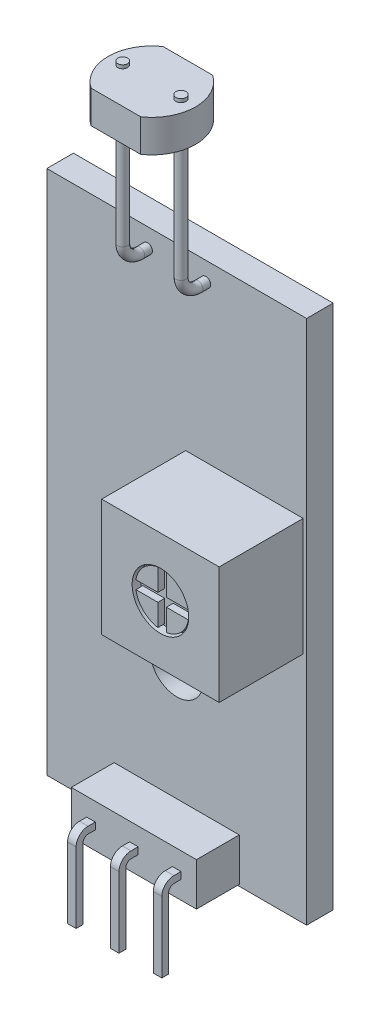
SolidWorks part; units mm, degrees
ref_plane "Plano frontal" through (0, 0, 0) normal (0, 0, 1) x (1, 0, 0)
ref_plane "Plano superior" through (0, 0, 0) normal (0, 1, 0) x (1, 0, 0)
ref_plane "Plano direito" through (0, 0, 0) normal (1, 0, 0) x (0, 0, -1)
sketch "Esboço1" plane through (0, 0, 0) normal (0, 0, 1) x (1, 0, 0)
  line L0 (0, -15.325) -> (0, -4.475) construction
  line L1 (7.575, 15.325) -> (-7.575, 15.325)
  line L2 (7.575, 15.325) -> (7.575, -15.325)
  line L3 (7.575, -15.325) -> (-7.575, -15.325)
  line L4 (-7.575, 15.325) -> (-7.575, -15.325)
  line L5 (7.575, 15.325) -> (-7.575, -15.325) construction
  line L6 (7.575, -15.325) -> (-7.575, 15.325) construction
  circle A0 centre (0, -6.025) radius 1.55
  point P0 (0, 0)
  dimension "D4" = 3.1
  dimension "D1" = 15.15
  dimension "D2" = 30.65
  dimension "D3" = 10.85
extrude "Ressalto-extrusão1" add sketch "Esboço1" along normal blind 1.55
sketch "Esboço2" plane through (0, 0, 0) normal (0, 0, 1) x (1, 0, 0)
  line L0 (7.575, -15.325) -> (7.575, 15.325) construction
  line L1 (7.375, 5.125) -> (0.525, 5.125)
  line L2 (7.375, 5.125) -> (7.375, -1.725)
  line L3 (7.375, -1.725) -> (0.525, -1.725)
  line L4 (0.525, 5.125) -> (0.525, -1.725)
  line L5 (-7.575, -15.325) -> (7.575, -15.325) construction
  dimension "D1" = 6.85
  dimension "D2" = 6.85
  dimension "D3" = 0.2
  dimension "D4" = 20.45
extrude "Ressalto-extrusão2" add sketch "Esboço2" along normal blind 6.45
sketch "Esboço3" plane through (0, 0, 6.45) normal (0, 0, 1) x (1, 0, 0)
  line L0 (0.525, -1.725) -> (7.375, 5.125) construction
  line L6 (3.7, 1.95) -> (2.4203, 1.95)
  line L7 (5.4797, 1.45) -> (4.2, 1.45)
  line L13 (5.4797, 1.95) -> (4.2, 1.95)
  line L15 (3.7, 1.45) -> (3.7, 0.1703)
  line L16 (4.2, 1.45) -> (4.2, 0.1703)
  line L19 (3.7, 3.2297) -> (3.7, 1.95)
  line L21 (4.2, 3.2297) -> (4.2, 1.95)
  line L22 (3.7, 1.45) -> (2.4203, 1.45)
  circle A0 centre (3.95, 1.7) radius 1.65
  arc A5 (5.4797, 1.95) -> (4.2, 3.2297) centre (3.95, 1.7) ccw
  circle A6 centre (3.95, 1.7) radius 1.55 construction
  arc A7 (2.4203, 1.45) -> (3.7, 0.1703) centre (3.95, 1.7) ccw
  arc A8 (4.2, 0.1703) -> (5.4797, 1.45) centre (3.95, 1.7) ccw
  arc A9 (3.7, 3.2297) -> (2.4203, 1.95) centre (3.95, 1.7) ccw
  point P7 (3.95, 1.7)
  dimension "D1" = 3.3
  dimension "D2" = 0.1
extrude "Corte-extrusão1" cut sketch "Esboço3" against normal blind 0.5
sketch "Esboço4" plane through (0, 0, 0) normal (0, 0, 1) x (1, 0, 0)
  line L2 (-3.65, -15.225) -> (-3.65, -12.725)
  line L3 (-3.65, -12.725) -> (3.65, -12.725)
  line L4 (3.65, -15.225) -> (3.65, -12.725)
  line L5 (0, -15.225) -> (0, -14.5169) construction
  line L6 (0, -15.225) -> (0, -11.5262) construction
  line L7 (-3.65, -15.225) -> (3.65, -15.225)
  line L8 (-7.575, -15.325) -> (7.575, -15.325) construction
  dimension "D1" = 7.3
  dimension "D2" = 0.1
  dimension "D3" = 2.5
extrude "Ressalto-extrusão3" add sketch "Esboço4" along normal blind 4.05
ref_plane "Plano1" through (0, 16.325, 0) normal (0, 1, 0) x (1, 0, 0)
sketch "Esboço9" plane through (0, 0, 6.45) normal (0, 0, 1) x (1, 0, 0)
  circle A1 centre (3.95, 1.7) radius 1.55
sketch "Esboço11" plane through (-3.65, 0, 0) normal (-1, 0, 0) x (0, 0, 1)
  line L0 (4.05, -13.975) -> (4.4674, -13.975) construction
  line L1 (4.05, -12.725) -> (4.05, -15.225) construction
  line L2 (4.9674, -14.475) -> (4.9674, -18.5951) construction
  line L3 (4.05, -14.175) -> (4.4674, -14.175)
  line L4 (4.7674, -14.475) -> (4.7674, -18.5951)
  line L5 (4.05, -13.775) -> (4.4674, -13.775)
  line L6 (5.1674, -14.475) -> (5.1674, -18.5951)
  line L7 (4.05, -13.775) -> (4.05, -14.175)
  line L8 (4.7674, -18.5951) -> (5.1674, -18.5951)
  arc A0 (4.4674, -13.975) -> (4.9674, -14.475) centre (4.4674, -14.475) cw construction
  arc A1 (4.4674, -14.175) -> (4.7674, -14.475) centre (4.4674, -14.475) cw
  arc A2 (4.4674, -13.775) -> (5.1674, -14.475) centre (4.4674, -14.475) cw
  dimension "D1" = 0.5
  dimension "D2" = 0.2
  dimension "D3" = 0.2
sketch "Esboço12" plane through (0, 0, 4.05) normal (0, 0, 1) x (1, 0, 0)
  line L0 (0, -12.725) -> (0, -12.2965) construction
  line L1 (-4.098, -13.3768) -> (-2.75, -13.3768)
  line L2 (-4.098, -13.3768) -> (-4.098, -19.3679)
  line L3 (-4.098, -19.3679) -> (-2.75, -19.3679)
  line L4 (-2.75, -13.3768) -> (-2.75, -19.3679)
  line L5 (3.7485, -13.3768) -> (2.75, -13.3768)
  line L6 (3.7485, -13.3768) -> (3.7485, -19.3679)
  line L7 (3.7485, -19.3679) -> (2.75, -19.3679)
  line L8 (2.75, -13.3768) -> (2.75, -19.3679)
  line L9 (-2.25, -13.3768) -> (-0.25, -13.3768)
  line L10 (-2.25, -13.3768) -> (-2.25, -19.3679)
  line L11 (-2.25, -19.3679) -> (-0.25, -19.3679)
  line L12 (-0.25, -13.3768) -> (-0.25, -19.3679)
  line L13 (2.25, -13.3768) -> (0.25, -13.3768)
  line L14 (2.25, -13.3768) -> (2.25, -19.3679)
  line L15 (2.25, -19.3679) -> (0.25, -19.3679)
  line L16 (0.25, -13.3768) -> (0.25, -19.3679)
  line L17 (3.65, -12.725) -> (-3.65, -12.725) construction
  line L18 (-0.25, -13.3768) -> (0.25, -13.3768) construction
  line L19 (0, -13.3768) -> (0, -14.2114) construction
  dimension "D1" = 0.5
  dimension "D2" = 0.5
  dimension "D3" = 0.5
  dimension "D4" = 2
  dimension "D5" = 2
extrude "Ressalto-extrusão5" add sketch "Esboço11" against normal up to vertex (7.3985 mm away) contours L6 L8 L4 A1 L3 L7 L5 A2 up to point (3.7485, -13.3768, 4.05)
extrude "Corte-extrusão2" cut sketch "Esboço12" along normal blind 10 contours L11 L12 L9 L10
extrude "Corte-extrusão3" cut sketch "Esboço9" against normal blind 0.1
ref_plane "Plano2" through (0, 22.325, 0) normal (0, 1, 0) x (1, 0, 0)
sketch "Esboço14" plane through (0, 22.325, 0) normal (0, 1, 0) x (1, 0, 0)
  line L0 (-1.4465, -0.9) -> (1.4465, -0.9) construction
  line L1 (-1.4465, -5.1) -> (1.4465, -5.1) construction
  line L2 (0, 0) -> (0, -3) construction
  circle A0 centre (-1.7, -3) radius 0.2856 construction
  circle A1 centre (1.7, -3) radius 0.2972 construction
  arc A2 (1.4465, -5.1) -> (1.4465, -0.9) centre (0, -3) ccw construction
  arc A3 (-1.4465, -0.9) -> (-1.4465, -5.1) centre (0, -3) ccw construction
  point P0 (0, -3)
  dimension "D1" = 3.4
  dimension "D2" = 1.7
  dimension "D3" = 3
sketch "Esboço17" plane through (0, 22.325, 0) normal (0, 1, 0) x (1, 0, 0)
  line L0 (-1.4465, -0.9) -> (1.4465, -0.9) construction
  line L1 (-1.4465, -5.1) -> (1.4465, -5.1) construction
  line L2 (-1.4465, -0.9) -> (1.4465, -0.9)
  line L3 (-1.4465, -5.1) -> (1.4465, -5.1)
  arc A0 (-1.4465, -0.9) -> (-1.4465, -5.1) centre (0, -3) ccw construction
  arc A1 (1.4465, -5.1) -> (1.4465, -0.9) centre (0, -3) ccw construction
  arc A2 (-1.4465, -0.9) -> (-1.4465, -5.1) centre (0, -3) ccw
  arc A3 (1.4465, -5.1) -> (1.4465, -0.9) centre (0, -3) ccw
extrude "Ressalto-extrusão6" add sketch "Esboço17" along normal blind 1.9 separate body
sketch "Esboço18" plane through (0, 24.225, 0) normal (0, 1, 0) x (1, 0, 0)
  circle A0 centre (1.7, -3) radius 0.2972 construction
  circle A1 centre (-1.7, -3) radius 0.2856 construction
  circle A2 centre (1.7, -3) radius 0.2972
  circle A3 centre (-1.7, -3) radius 0.2856
extrude "Ressalto-extrusão7" add sketch "Esboço18" along normal blind 0.2
ref_plane "Plano3" through (-1.7, 0, 0) normal (-1, 0, 0) x (0, 0, 1)
sketch "Esboço19" plane through (-1.7, 0, 0) normal (-1, 0, 0) x (0, 0, 1)
  line L0 (3, 22.325) -> (3, 15.2274)
  line L1 (1.55, 14.2274) -> (2, 14.2274)
  arc A0 (3, 15.2274) -> (2, 14.2274) centre (2, 15.2274) cw
  dimension "D1" = 1
sketch "Esboço24" plane through (0, 22.325, 0) normal (0, -1, 0) x (1, 0, 0)
  circle A0 centre (-1.7, 3) radius 0.2856 construction
  circle A1 centre (-1.7, 3) radius 0.2856
sketch "Esboço25" plane through (0, 22.325, 0) normal (0, -1, 0) x (1, 0, 0)
  circle A0 centre (-1.7, 3) radius 0.2856 construction
  circle A1 centre (-1.7, 3) radius 0.2856
sweep "Varredura5" add profiles "Esboço25" path "Esboço19"
ref_plane "Plano4" through (0, 0, 0) normal (-1, 0, 0) x (0, 0, 1)
mirror "Espelhar1" about plane through (0, 0, 0) normal (-1, 0, 0) of "Varredura5"
